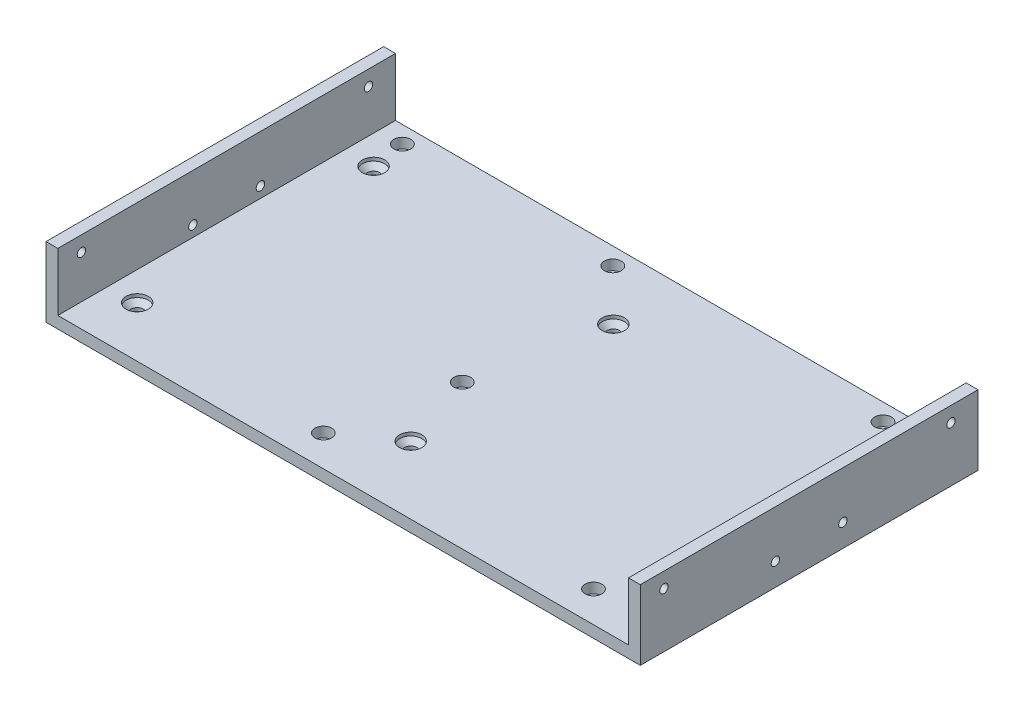
SolidWorks part; units mm, degrees
material "Д16 ГОСТ 4784-97"
ref_plane "Спереди" through (0, 0, 0) normal (0, 0, 1) x (1, 0, 0)
ref_plane "Сверху" through (0, 0, 0) normal (0, 1, 0) x (1, 0, 0)
ref_plane "Справа" through (0, 0, 0) normal (1, 0, 0) x (0, 0, -1)
sketch "Эскиз1" plane through (0, 0, 0) normal (0, 0, 1) x (1, 0, 0)
  line L0 (0, 20.7) -> (0, 0)
  line L1 (0, 0) -> (176, 0)
  line L2 (176, 0) -> (176, 20.7)
  dimension "D1" = 176
  dimension "D2" = 20.7
extrude "Вытянуть-Тонкостенный1" add sketch "Эскиз1" along normal blind 100 thin thin type one direction reverse wall 3.5
hole_wizard "Диаметр отверстия Ø2.5 (2.5)1" positions "Эскиз3" profile "Эскиз2" hole size "Ø2.5" standard "ГОСТ"
sketch "Эскиз3" plane through (0, 0, 0) normal (0, -1, 0) x (-1, 0, 0)
  line L0 (0, -100) -> (0, 0) construction
  line L1 (0, -100) -> (-176, -100) construction
  line L2 (-176, -100) -> (-176, 0) construction
  line L3 (0, 0) -> (-176, 0) construction
  point P0 (-5, -92.5)
  point P2 (-171, -7.5)
  dimension "D1" = 5
  dimension "D2" = 7.5
  dimension "D3" = 5
  dimension "D4" = 7.5
sketch "Эскиз2" plane through (5, 0, 92.5) normal (1, 0, 0) x (0, 0, -1)
  line L0 (0, 0) -> (0, 3)
  line L1 (0, 3) -> (1.25, 3)
  line L2 (1.25, 3) -> (1.25, 0)
  line L5 (1.25, 0) -> (0, 0)
  line L10 (0, 3) -> (-1.25, 3) construction
  line L11 (0, -6.35) -> (0, 107.95) construction
  dimension "Диаметр отверстия" = 2.5
  dimension "Глубина отверстия" = 3
  dimension "Угол заточки сверла" = 180
hole_wizard "Отверстие обработанное метчиком M2,51" positions "Эскиз5" profile "Эскиз4" tap size "M2,5" standard "ГОСТ"
sketch "Эскиз5" plane through (0, 0, 0) normal (0, -1, 0) x (-1, 0, 0)
  line L0 (0, -100) -> (0, 0) construction
  line L1 (0, -100) -> (-176, -100) construction
  point P0 (-19.45, -93.75)
  point P2 (-60.45, -93.75)
  point P4 (-136.45, -93.75)
  point P6 (-136.45, -6.75)
  point P8 (-49.25, -6.75)
  point P10 (-19.45, -6.75)
  dimension "D1" = 19.45
  dimension "D2" = 41
  dimension "D3" = 76
  dimension "D4" = 87
  dimension "D5" = 6.25
  dimension "D6" = 49.25
sketch "Эскиз4" plane through (19.45, 0, 93.75) normal (1, 0, 0) x (0, 0, -1)
  line L0 (0, 0) -> (0, 3)
  line L1 (0, 3) -> (1.025, 3)
  line L2 (1.025, 3) -> (1.025, 0)
  line L5 (1.025, 0) -> (0, 0)
  line L10 (0, 3) -> (-1.025, 3) construction
  line L11 (0, -6.35) -> (0, 107.95) construction
  dimension "Диаметр сверла" = 2.05
  dimension "Глубина сверла" = 3
  dimension "Угол заточки сверла" = 180
cosmetic thread "Отверстие резьбы1" parameters "D1"=2.5, "D2"=2.5
cosmetic thread "Отверстие резьбы2" parameters "D1"=2.5, "D2"=2.5
cosmetic thread "Отверстие резьбы3" parameters "D1"=2.5, "D2"=2.5
cosmetic thread "Отверстие резьбы4" parameters "D1"=2.5, "D2"=2.5
cosmetic thread "Отверстие резьбы5" parameters "D1"=2.5, "D2"=2.5
cosmetic thread "Отверстие резьбы6" parameters "D1"=2.5, "D2"=2.5
hole_wizard "Отверстие обработанное метчиком M31" positions "Эскиз7" profile "Эскиз6" tap size "M3" standard "ГОСТ"
sketch "Эскиз7" plane through (0, 0, 0) normal (0, -1, 0) x (-1, 0, 0)
  line L0 (0, -100) -> (0, 0) construction
  line L1 (0, -100) -> (-176, -100) construction
  point P0 (-28, -87.5)
  point P2 (-88, -87.5)
  point P4 (-148, -87.5)
  point P6 (-148, -12.5)
  point P8 (-88, -12.5)
  point P10 (-28, -12.5)
  dimension "D1" = 28
  dimension "D2" = 60
  dimension "D3" = 60
  dimension "D4" = 75
  dimension "D5" = 12.5
sketch "Эскиз6" plane through (28, 0, 87.5) normal (1, 0, 0) x (0, 0, -1)
  line L0 (0, 0) -> (0, 3)
  line L1 (0, 3) -> (1.25, 3)
  line L2 (1.25, 3) -> (1.25, 0)
  line L5 (1.25, 0) -> (0, 0)
  line L10 (0, 3) -> (-1.25, 3) construction
  line L11 (0, -6.35) -> (0, 107.95) construction
  dimension "Диаметр сверла" = 2.5
  dimension "Глубина сверла" = 3
  dimension "Угол заточки сверла" = 180
cosmetic thread "Отверстие резьбы7" parameters "D1"=2.5, "D2"=3
cosmetic thread "Отверстие резьбы8" parameters "D1"=2.5, "D2"=3
cosmetic thread "Отверстие резьбы9" parameters "D1"=2.5, "D2"=3
cosmetic thread "Отверстие резьбы10" parameters "D1"=2.5, "D2"=3
cosmetic thread "Отверстие резьбы11" parameters "D1"=2.5, "D2"=3
cosmetic thread "Отверстие резьбы12" parameters "D1"=2.5, "D2"=3
hole_wizard "Отверстие обработанное метчиком M41" positions "Эскиз9" profile "Эскиз8" tap size "M4" standard "ГОСТ"
sketch "Эскиз9" plane through (0, 0, 0) normal (0, -1, 0) x (-1, 0, 0)
  line L0 (0, -100) -> (0, 0) construction
  line L1 (0, -100) -> (-176, -100) construction
  point P0 (-50.5, -87.5)
  point P2 (-125.7, -87.5)
  point P4 (-125.7, -12.5)
  point P6 (-50.5, -12.5)
  dimension "D1" = 50.5
  dimension "D2" = 12.5
  dimension "D3" = 75.2
  dimension "D4" = 75
sketch "Эскиз8" plane through (50.5, 0, 87.5) normal (1, 0, 0) x (0, 0, -1)
  line L0 (0, 0) -> (0, 3)
  line L1 (0, 3) -> (1.65, 3)
  line L2 (1.65, 3) -> (1.65, 0)
  line L5 (1.65, 0) -> (0, 0)
  line L10 (0, 3) -> (-1.65, 3) construction
  line L11 (0, -6.35) -> (0, 107.95) construction
  dimension "Диаметр сверла" = 3.3
  dimension "Глубина сверла" = 3
  dimension "Угол заточки сверла" = 180
cosmetic thread "Отверстие резьбы13" parameters "D1"=2.5, "D2"=4
cosmetic thread "Отверстие резьбы14" parameters "D1"=2.5, "D2"=4
cosmetic thread "Отверстие резьбы15" parameters "D1"=2.5, "D2"=4
cosmetic thread "Отверстие резьбы16" parameters "D1"=2.5, "D2"=4
hole_wizard "Отверстие обработанное метчиком M32" positions "Эскиз11" profile "Эскиз10" tap size "M3" standard "ГОСТ"
sketch "Эскиз11" plane through (176, 0, 0) normal (1, 0, 0) x (0, 0, -1)
  line L0 (-100, 0) -> (-100, 20.7) construction
  line L1 (-100, 20.7) -> (0, 20.7) construction
  point P0 (-93, 16.2)
  point P2 (-60, 6.7)
  point P4 (-40, 6.7)
  point P6 (-8, 16.2)
  dimension "D1" = 7
  dimension "D2" = 40
  dimension "D3" = 20
  dimension "D4" = 85
  dimension "D5" = 4.5
  dimension "D6" = 14
sketch "Эскиз10" plane through (176, 16.2, 93) normal (0, 1, 0) x (0, 0, -1)
  line L0 (0, 0) -> (0, 3.5)
  line L1 (0, 3.5) -> (1.25, 3.5)
  line L2 (1.25, 3.5) -> (1.25, 0)
  line L5 (1.25, 0) -> (0, 0)
  line L10 (0, 3.5) -> (-1.25, 3.5) construction
  line L11 (0, -6.35) -> (0, 107.95) construction
  dimension "Диаметр сверла" = 2.5
  dimension "Глубина сверла" = 3.5
  dimension "Угол заточки сверла" = 180
cosmetic thread "Отверстие резьбы17" parameters "D1"=3, "D2"=3
cosmetic thread "Отверстие резьбы18" parameters "D1"=3, "D2"=3
cosmetic thread "Отверстие резьбы19" parameters "D1"=3, "D2"=3
cosmetic thread "Отверстие резьбы20" parameters "D1"=3, "D2"=3
hole_wizard "Отверстие обработанное метчиком M33" positions "Эскиз13" profile "Эскиз12" tap size "M3" standard "ГОСТ"
sketch "Эскиз13" plane through (0, 0, 0) normal (-1, 0, 0) x (0, 0, 1)
  point P0 (93, 16.2)
  point P3 (60, 6.7)
  point P6 (40, 6.7)
  point P9 (8, 16.2)
sketch "Эскиз12" plane through (0, 16.2, 93) normal (0, 1, 0) x (0, 0, 1)
  line L0 (0, 0) -> (0, 5.5)
  line L1 (0, 5.5) -> (1.25, 5.5)
  line L2 (1.25, 5.5) -> (1.25, 0)
  line L5 (1.25, 0) -> (0, 0)
  line L10 (0, 5.5) -> (-1.25, 5.5) construction
  line L11 (0, -6.35) -> (0, 107.95) construction
  dimension "Диаметр сверла" = 2.5
  dimension "Глубина сверла" = 5.5
  dimension "Угол заточки сверла" = 180
cosmetic thread "Отверстие резьбы21" parameters "D1"=3, "D2"=3
cosmetic thread "Отверстие резьбы22" parameters "D1"=3, "D2"=3
cosmetic thread "Отверстие резьбы23" parameters "D1"=3, "D2"=3
cosmetic thread "Отверстие резьбы24" parameters "D1"=3, "D2"=3
hole_wizard "Зенковка для винта с потайной головкой M31" positions "Эскиз17" profile "Эскиз14" countersink size "M3" standard "ГОСТ" end condition up to next
sketch "Эскиз17" plane through (0, 3.5, 0) normal (0, 1, 0) x (1, 0, 0)
  line L0 (3.5, -50) -> (172.5, -50) construction
  line L1 (3.5, -100) -> (3.5, 0) construction
  line L2 (172.5, -100) -> (172.5, 0) construction
  line L4 (88, -20) -> (88, -50) construction
  line L6 (3.5, -100) -> (172.5, -100) construction
  line L8 (0, -100) -> (0, 0) construction
  point P0 (12, -15)
  point P2 (88, -20)
  point P4 (164, -15)
  point P6 (12, -85)
  point P8 (88, -80)
  point P10 (164, -85)
  dimension "D1" = 15
  dimension "D2" = 85
  dimension "D3" = 12
  dimension "D4" = 164
  dimension "D5" = 20
  dimension "D6" = 80
sketch "Эскиз14" plane through (12, 3.5, 15) normal (1, 0, 0) x (0, 0, 1)
  line L0 (0, 0) -> (0, 3.5)
  line L1 (0, 3.5) -> (1.8, 3.5)
  line L2 (1.8, 3.5) -> (1.8, 2.5)
  line L3 (1.8, 2.5) -> (3.3, 1)
  line L4 (3.3, 1) -> (3.3, 0)
  line L6 (3.3, 0) -> (0, 0)
  line L7 (-1.8, 2.5) -> (-3.3, 1) construction
  line L11 (0, -6.35) -> (0, 107.95) construction
  dimension "Диаметр сквозного отверстия" = 3.6
  dimension "Глубина сквозного отверстия" = 3.5
  dimension "Диаметр зенковки" = 6.6
  dimension "Угол зенковки" = 90
  dimension "Утопленность" = 1
hole_wizard "Диаметр отверстия Ø5.0 (5)1" positions "Эскиз19" profile "Эскиз18" hole size "Ø5.0" standard "ГОСТ"
sketch "Эскиз19" plane through (0, 3.5, 0) normal (0, 1, 0) x (1, 0, 0)
  point P0 (165.42, -5.05)
  point P3 (152.97, -5.12)
  point P6 (72.96, -5.12)
  point P9 (10.58, -5.05)
  point P12 (80.5, -57.25)
  point P15 (72.96, -90.84)
  point P18 (152.97, -90.84)
sketch "Эскиз18" plane through (165.42, 3.5, 5.05) normal (1, 0, 0) x (0, 0, 1)
  line L0 (0, 0) -> (0, 3)
  line L1 (0, 3) -> (2.5, 3)
  line L2 (2.5, 3) -> (2.5, 0)
  line L5 (2.5, 0) -> (0, 0)
  line L10 (0, 3) -> (-2.5, 3) construction
  line L11 (0, -6.35) -> (0, 107.95) construction
  dimension "Диаметр отверстия" = 5
  dimension "Глубина отверстия" = 3
  dimension "Угол заточки сверла" = 180
sketch "Эскиз21" plane through (0, 3.5, 0) normal (0, 1, 0) x (1, 0, 0)
  line L0 (23, 0) -> (23, -100) construction
  line L1 (3.5, 0) -> (172.5, 0) construction
  line L2 (3.5, -100) -> (172.5, -100) construction
  line L3 (0, -100) -> (0, 0) construction
  line L4 (33, -100) -> (33, 0) construction
  line L5 (0, -100) -> (176, -100) construction
  line L6 (0, 0) -> (176, 0) construction
  line L7 (36, 0) -> (38, 0)
  line L8 (22, -100) -> (24, -100)
  line L9 (22, -100) -> (22, 0)
  line L10 (22, 0) -> (24, 0)
  line L11 (24, -100) -> (24, 0)
  line L12 (32, 0) -> (34, 0)
  line L13 (32, 0) -> (32, -100)
  line L14 (32, -100) -> (34, -100)
  line L15 (34, 0) -> (34, -100)
  line L16 (36, 0) -> (36, -100)
  line L17 (36, -100) -> (38, -100)
  line L18 (38, 0) -> (38, -100)
  line L19 (37, -100) -> (37, 0) construction
  line L20 (40, 0) -> (42, 0)
  line L21 (40, 0) -> (40, -100)
  line L22 (40, -100) -> (42, -100)
  line L23 (42, 0) -> (42, -100)
  line L24 (41, -100) -> (41, 0) construction
  dimension "D1" = 23
  dimension "D2" = 10
  dimension "D3" = 2
  dimension "D5" = 2
  dimension "D4" = 3
extrude "Вырез-Вытянуть1" [suppressed] cut sketch "Эскиз21" against normal blind 1
sketch "Эскиз22" plane through (0, 3.5, 0) normal (0, 1, 0) x (1, 0, 0)
  line L0 (3.5, 0) -> (172.5, 0) construction
  line L1 (119.7, 0) -> (121.7, 0)
  line L2 (119.7, 0) -> (119.7, -100)
  line L3 (119.7, -100) -> (121.7, -100)
  line L4 (121.7, 0) -> (121.7, -100)
  line L5 (3.5, -100) -> (172.5, -100) construction
  line L6 (120.7, 0) -> (120.7, -100) construction
  line L9 (130.7, -100) -> (130.7, 0) construction
  line L10 (0, -100) -> (176, -100) construction
  line L11 (0, 0) -> (176, 0) construction
  line L12 (125.7, -87.5) -> (125.7, -107.3276) construction
  line L13 (141.45, -100) -> (141.45, 0) construction
  line L14 (129.7, -100) -> (131.7, -100)
  line L15 (129.7, -100) -> (129.7, 0)
  line L16 (129.7, 0) -> (131.7, 0)
  line L17 (131.7, -100) -> (131.7, 0)
  line L18 (136.45, -93.75) -> (136.45, -102.9084) construction
  line L20 (140.45, -100) -> (142.45, -100)
  line L21 (140.45, -100) -> (140.45, 0)
  line L22 (140.45, 0) -> (142.45, 0)
  line L23 (142.45, -100) -> (142.45, 0)
  dimension "D1" = 2
  dimension "D2" = 5
  dimension "D3" = 5
  dimension "D4" = 5
extrude "Вырез-Вытянуть2" [suppressed] cut sketch "Эскиз22" against normal blind 1
sketch "Эскиз23" plane through (0, 20.7, 0) normal (0, 1, 0) x (1, 0, 0)
  line L0 (176, -100) -> (176, 0) construction
  line L1 (172.5, -100) -> (176, -100)
  line L2 (172.5, -100) -> (172.5, -65)
  line L3 (172.5, -65) -> (176, -65)
  line L4 (176, -100) -> (176, -65)
  dimension "D1" = 35
extrude "Вырез-Вытянуть3" [suppressed] cut sketch "Эскиз23" against normal blind 3
